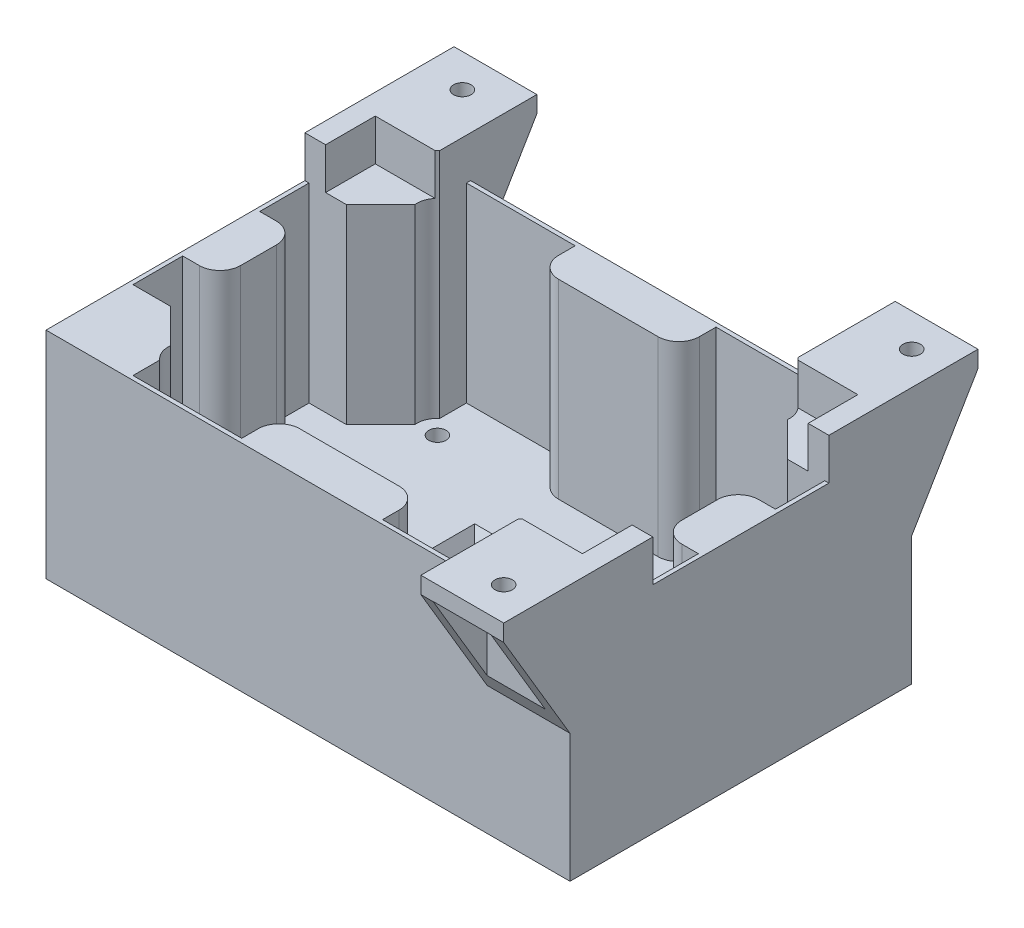
SolidWorks part; units mm, degrees
ref_plane "Спереди" through (0, 0, 0) normal (0, 0, 1) x (1, 0, 0)
ref_plane "Сверху" through (0, 0, 0) normal (0, 1, 0) x (1, 0, 0)
ref_plane "Справа" through (0, 0, 0) normal (1, 0, 0) x (0, 0, -1)
ref_plane "Плоскость4" through (0, 77.196, 0) normal (0, 1, 0) x (1, 0, 0)
sketch "Эскиз1" plane through (0, 77.196, 0) normal (0, 1, 0) x (1, 0, 0)
  line L0 (1.559, -48.2731) -> (128.059, -48.2731)
  line L1 (128.059, -48.2731) -> (128.059, -130.7731)
  line L2 (128.059, -130.7731) -> (1.559, -130.7731)
  line L3 (1.559, -130.7731) -> (1.559, -48.2731)
  line L4 (49.809, -75.5231) -> (79.809, -75.5231)
  line L5 (78.809, -75.5231) -> (79.809, -75.5231) construction
  line L6 (79.809, -75.5231) -> (79.809, -103.5231)
  line L8 (79.809, -103.5231) -> (49.809, -103.5231)
  line L9 (50.809, -103.5231) -> (49.809, -103.5231) construction
  line L10 (49.809, -103.5231) -> (49.809, -75.5231)
  circle A0 centre (24.809, -59.5231) radius 2.1
  circle A1 centre (104.809, -59.5231) radius 2.1
  circle A2 centre (104.809, -119.5231) radius 2.1
  circle A3 centre (24.809, -119.5231) radius 2.1
extrude "Бобышка-Вытянуть2" add sketch "Эскиз1" along normal blind 6
chamfer "Фаска1" distance 2 angle 60 4 edges at (49.809, 83.196, 89.5231) (64.809, 83.196, 103.5231) (79.809, 83.196, 89.5231) (64.809, 83.196, 75.5231)
ref_plane "Плоскость5" through (0, 83.196, 0) normal (0, 1, 0) x (1, 0, 0)
sketch "Эскиз2" plane through (0, 83.196, 0) normal (0, 1, 0) x (1, 0, 0)
  line L0 (1.559, -48.2731) -> (21.559, -48.2731)
  line L1 (128.059, -48.2731) -> (1.559, -48.2731) construction
  line L2 (21.559, -48.2731) -> (21.559, -58.2731)
  line L3 (1.559, -48.2731) -> (1.559, -68.2731)
  line L5 (1.559, -68.2731) -> (11.559, -68.2731)
  line L6 (1.559, -48.2731) -> (1.559, -130.7731) construction
  line L7 (11.559, -68.2731) -> (21.559, -58.2731)
  line L8 (128.059, -48.2731) -> (108.059, -48.2731)
  line L9 (108.059, -48.2731) -> (108.059, -58.2731)
  line L10 (128.059, -48.2731) -> (128.059, -68.2731)
  line L11 (128.059, -130.7731) -> (128.059, -48.2731) construction
  line L12 (128.059, -68.2731) -> (118.059, -68.2731)
  line L13 (118.059, -68.2731) -> (108.059, -58.2731)
  line L14 (1.559, -130.7731) -> (1.559, -110.7731)
  line L15 (1.559, -110.7731) -> (11.559, -110.7731)
  line L16 (1.559, -130.7731) -> (21.559, -130.7731)
  line L17 (1.559, -130.7731) -> (128.059, -130.7731) construction
  line L18 (21.559, -130.7731) -> (21.559, -120.7731)
  line L19 (21.559, -120.7731) -> (11.559, -110.7731)
  line L20 (128.059, -130.7731) -> (128.059, -110.7731)
  line L21 (128.059, -110.7731) -> (118.059, -110.7731)
  line L22 (128.059, -130.7731) -> (108.059, -130.7731)
  line L23 (108.059, -130.7731) -> (108.059, -120.7731)
  line L24 (108.059, -120.7731) -> (118.059, -110.7731)
  line L27 (1.559, -98.7731) -> (1.559, -80.1738)
  line L32 (128.059, -98.7731) -> (128.059, -80.1738)
  line L33 (47.809, -48.2731) -> (81.809, -48.2731)
  line L39 (81.809, -130.7731) -> (47.809, -130.7731)
  line L40 (-8.25, -130.7731) -> (8.25, -130.7731) construction
  line L42 (1.559, -80.1738) -> (11.559, -80.1738)
  line L43 (11.559, -80.1738) -> (11.559, -98.7731)
  line L44 (11.559, -98.7731) -> (1.559, -98.7731)
  line L45 (47.809, -48.2731) -> (47.809, -58.2731)
  line L46 (47.809, -58.2731) -> (81.809, -58.2731)
  line L47 (81.809, -58.2731) -> (81.809, -48.2731)
  line L48 (128.059, -80.1738) -> (118.059, -80.1738)
  line L49 (118.059, -80.1738) -> (118.059, -98.7731)
  line L50 (118.059, -98.7731) -> (128.059, -98.7731)
  line L51 (81.809, -130.7731) -> (81.809, -120.7731)
  line L52 (81.809, -120.7731) -> (47.809, -120.7731)
  line L53 (47.809, -120.7731) -> (47.809, -130.7731)
  line L54 (1.559, -68.2731) -> (1.559, -80.1738)
  line L55 (1.559, -80.1738) -> (2.559, -80.1738)
  line L56 (2.559, -80.1738) -> (2.559, -68.2731)
  line L57 (2.559, -68.2731) -> (1.559, -68.2731)
  line L58 (1.559, -98.7731) -> (2.559, -98.7731)
  line L59 (2.559, -98.7731) -> (2.559, -110.7731)
  line L60 (2.559, -110.7731) -> (1.559, -110.7731)
  line L61 (1.559, -98.7731) -> (1.559, -110.7731)
  line L62 (21.559, -130.7731) -> (21.559, -129.7731)
  line L63 (21.559, -129.7731) -> (47.809, -129.7731)
  line L64 (47.809, -129.7731) -> (47.809, -130.7731)
  line L65 (47.809, -130.7731) -> (21.559, -130.7731)
  line L66 (108.059, -130.7731) -> (108.059, -129.7731)
  line L67 (108.059, -129.7731) -> (81.809, -129.7731)
  line L68 (81.809, -129.7731) -> (81.809, -130.7731)
  line L69 (81.809, -130.7731) -> (108.059, -130.7731)
  line L70 (128.059, -68.2731) -> (127.059, -68.2731)
  line L71 (127.059, -68.2731) -> (127.059, -80.1738)
  line L72 (127.059, -80.1738) -> (128.059, -80.1738)
  line L73 (128.059, -80.1738) -> (128.059, -68.2731)
  line L74 (128.059, -110.7731) -> (127.059, -110.7731)
  line L75 (127.059, -110.7731) -> (127.059, -98.7731)
  line L76 (127.059, -98.7731) -> (128.059, -98.7731)
  line L77 (128.059, -98.7731) -> (128.059, -110.7731)
  line L78 (108.059, -48.2731) -> (108.059, -49.2731)
  line L79 (108.059, -49.2731) -> (81.809, -49.2731)
  line L80 (81.809, -49.2731) -> (81.809, -48.2731)
  line L81 (108.059, -48.2731) -> (81.809, -48.2731)
  line L82 (47.809, -48.2731) -> (47.809, -49.2731)
  line L83 (47.809, -49.2731) -> (21.559, -49.2731)
  line L84 (47.809, -48.2731) -> (21.559, -48.2731)
  line L85 (21.559, -48.2731) -> (21.559, -49.2731)
extrude "Бобышка-Вытянуть3" add sketch "Эскиз2" along normal blind 46 contours L5 L7 L2 L0 L3 | L46 L47 L33 L45 | L13 L12 L10 L8 L9 | L49 L50 L32 L48 | L24 L23 L22 L20 L21 | L52 L53 L39 L51 | L18 L19 L15 L14 L16 | L42 L56 L5 L54 | L44 L43 L42 L27 | L44 L61 L15 L59 | L65 L53 L63 L18 | L51 L69 L23 L67 | L77 L50 L75 L21 | L48 L73 L12 L71 | L9 L81 L47 L79 | L45 L84 L2 L83
ref_plane "Плоскость6" through (0, 129.196, 0) normal (0, 1, 0) x (1, 0, 0)
sketch "Эскиз3" plane through (0, 129.196, 0) normal (0, 1, 0) x (1, 0, 0)
  line L6 (6.559, -68.2731) -> (6.559, -56.2731)
  line L7 (6.559, -56.2731) -> (21.559, -56.2731)
  line L8 (21.559, -56.2731) -> (21.559, -48.2731)
  line L9 (21.559, -48.2731) -> (1.559, -48.2731)
  line L10 (1.559, -48.2731) -> (1.559, -68.2731)
  line L11 (1.559, -68.2731) -> (6.559, -68.2731)
  line L12 (123.059, -68.2731) -> (123.059, -56.2731)
  line L13 (123.059, -56.2731) -> (108.059, -56.2731)
  line L14 (108.059, -56.2731) -> (108.059, -48.2731)
  line L15 (108.059, -48.2731) -> (128.059, -48.2731)
  line L18 (128.059, -48.2731) -> (128.059, -68.2731)
  line L19 (128.059, -68.2731) -> (123.059, -68.2731)
  line L20 (123.059, -110.7731) -> (123.059, -122.7731)
  line L21 (123.059, -122.7731) -> (108.059, -122.7731)
  line L22 (108.059, -122.7731) -> (108.059, -130.7731)
  line L24 (108.059, -130.7731) -> (128.059, -130.7731)
  line L26 (128.059, -130.7731) -> (128.059, -110.7731)
  line L27 (128.059, -110.7731) -> (123.059, -110.7731)
extrude "Бобышка-Вытянуть4" add sketch "Эскиз3" along normal blind 10
ref_plane "Плоскость7" through (1.559, 0, 0) normal (-1, 0, 0) x (0, 0, 1)
sketch "Эскиз4" plane through (1.559, 0, 0) normal (-1, 0, 0) x (0, 0, 1)
  line L11 (48.2731, 139.196) -> (48.2731, 108.196)
  line L12 (48.2731, 139.196) -> (48.2731, 77.196) construction
  line L18 (48.2731, 139.196) -> (32.2731, 139.196)
  line L19 (32.2731, 139.196) -> (32.2731, 135.146)
  line L20 (32.2731, 135.146) -> (48.2731, 108.196)
extrude "Бобышка-Вытянуть7" add sketch "Эскиз4" against normal blind 20
ref_plane "Плоскость8" through (128.059, 0, 0) normal (1, 0, 0) x (0, 0, -1)
sketch "Эскиз5" plane through (128.059, 0, 0) normal (1, 0, 0) x (0, 0, -1)
  line L1 (-130.7731, 139.196) -> (-130.7731, 108.146)
  line L2 (-130.7731, 108.146) -> (-146.7731, 135.146)
  line L3 (-146.7731, 135.146) -> (-146.7731, 139.196)
  line L9 (-48.2731, 139.196) -> (-48.2731, 108.196)
  line L10 (-48.2731, 139.196) -> (-48.2731, 77.196) construction
  line L11 (-48.2731, 108.196) -> (-32.2731, 135.146)
  line L12 (-32.2731, 135.146) -> (-32.2731, 139.196)
  line L13 (-32.2731, 139.196) -> (-48.2731, 139.196)
  line L14 (-146.7731, 139.196) -> (-130.7731, 139.196)
extrude "Бобышка-Вытянуть8" add sketch "Эскиз5" against normal blind 20
ref_plane "Плоскость9" through (0, 139.196, 0) normal (0, 1, 0) x (1, 0, 0)
sketch "Эскиз6" plane through (0, 139.196, 0) normal (0, 1, 0) x (1, 0, 0)
  circle A0 centre (120.059, -40.2731) radius 2.1
  circle A1 centre (11.559, -40.2731) radius 2.1
  circle A2 centre (11.559, -138.7731) radius 2.1
  circle A3 centre (120.059, -138.7731) radius 2.1
extrude "Вырез-Вытянуть1" cut sketch "Эскиз6" against normal through all both and the other way through all
ref_plane "Плоскость10" through (0, 77.196, 0) normal (0, -1, 0) x (-1, 0, 0)
sketch "Эскиз7" plane through (0, 77.196, 0) normal (0, -1, 0) x (-1, 0, 0)
  line L0 (-18.559, -45.2731) -> (-18.559, -31.5092)
  line L2 (-18.559, -31.5092) -> (-4.559, -31.5092)
  line L3 (-18.559, -45.2731) -> (-4.559, -45.2731)
  line L4 (-4.559, -45.2731) -> (-4.559, -31.5092)
  line L5 (-111.059, -45.2731) -> (-111.059, -31.5997)
  line L7 (-111.059, -31.5997) -> (-125.059, -31.5997)
  line L8 (-125.059, -31.5997) -> (-125.059, -45.2731)
  line L9 (-125.059, -45.2731) -> (-111.059, -45.2731)
  line L10 (-125.059, -133.7731) -> (-125.059, -147.7887)
  line L12 (-125.059, -147.7887) -> (-111.059, -147.7887)
  line L13 (-125.059, -133.7731) -> (-111.059, -133.7731)
  line L14 (-111.059, -133.7731) -> (-111.059, -147.7887)
  line L15 (-4.559, -147.6651) -> (-4.559, -133.7731)
  line L16 (-4.559, -133.7731) -> (-18.559, -133.7731)
  line L17 (-18.559, -133.7731) -> (-18.559, -147.6651)
  line L18 (-18.559, -147.6651) -> (-4.559, -147.6651)
extrude "Вырез-Вытянуть2" cut sketch "Эскиз7" against normal blind 58
fillet "Скругление1" radius 5 8 edges at (11.559, 106.196, 98.7731) (11.559, 106.196, 80.1738) (47.809, 106.196, 120.7731) (81.809, 106.196, 120.7731) (118.059, 106.196, 98.7731) (118.059, 106.196, 80.1738) (47.809, 106.196, 58.2731) (81.809, 106.196, 58.2731)
sketch "Эскиз9" plane through (0, 83.196, 0) normal (0, 1, 0) x (1, 0, 0)
  circle A0 centre (24.809, -59.5231) radius 5
  circle A1 centre (104.809, -59.5231) radius 5
  circle A2 centre (104.809, -119.5231) radius 5
  circle A3 centre (24.809, -119.5231) radius 5
extrude "Вырез-Вытянуть4" cut sketch "Эскиз9" along normal through all
